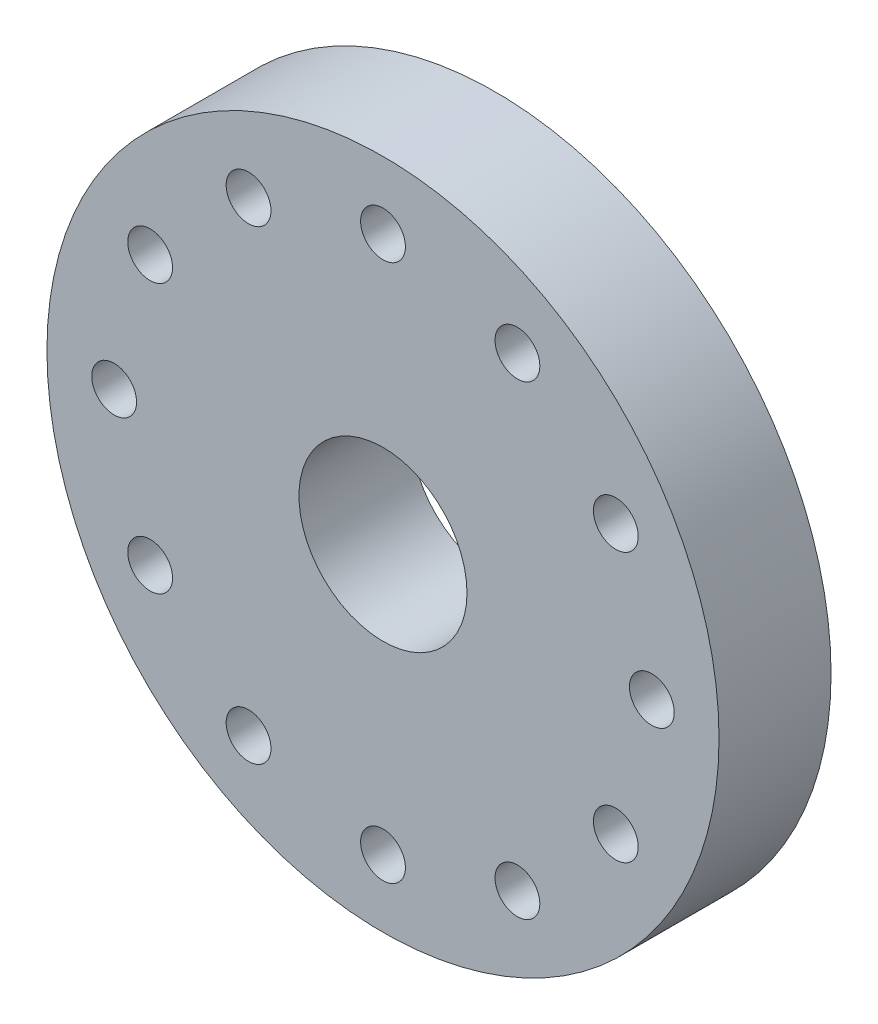
SolidWorks part; units mm, degrees
ref_plane "前视基准面" through (0, 0, 0) normal (0, 0, 1) x (1, 0, 0)
ref_plane "上视基准面" through (0, 0, 0) normal (0, 1, 0) x (1, 0, 0)
ref_plane "右视基准面" through (0, 0, 0) normal (1, 0, 0) x (0, 0, -1)
sketch "草图1" plane through (0, 0, 0) normal (0, 0, 1) x (1, 0, 0)
  circle A0 centre (0, 0) radius 30
extrude "凸台-拉伸1" add sketch "草图1" along normal blind 10
sketch "草图2" plane through (0, 0, 0) normal (0, 0, 1) x (1, 0, 0)
  circle A0 centre (0, 0) radius 7.5
extrude "切除-拉伸1" cut sketch "草图2" along normal through all
sketch "草图3" plane through (0, 0, 0) normal (0, 0, 1) x (1, 0, 0)
  circle A0 centre (24, 0) radius 2
  circle A1 centre (20.7846, 12) radius 2
  circle A2 centre (12, 20.7846) radius 2
  circle A3 centre (0, 24) radius 2
  circle A4 centre (-12, 20.7846) radius 2
  circle A5 centre (-20.7846, 12) radius 2
  circle A6 centre (-24, 0) radius 2
  circle A7 centre (-20.7846, -12) radius 2
  circle A8 centre (-12, -20.7846) radius 2
  circle A9 centre (0, -24) radius 2
  circle A10 centre (12, -20.7846) radius 2
  circle A11 centre (20.7846, -12) radius 2
extrude "切除-拉伸2" cut sketch "草图3" along normal through all
